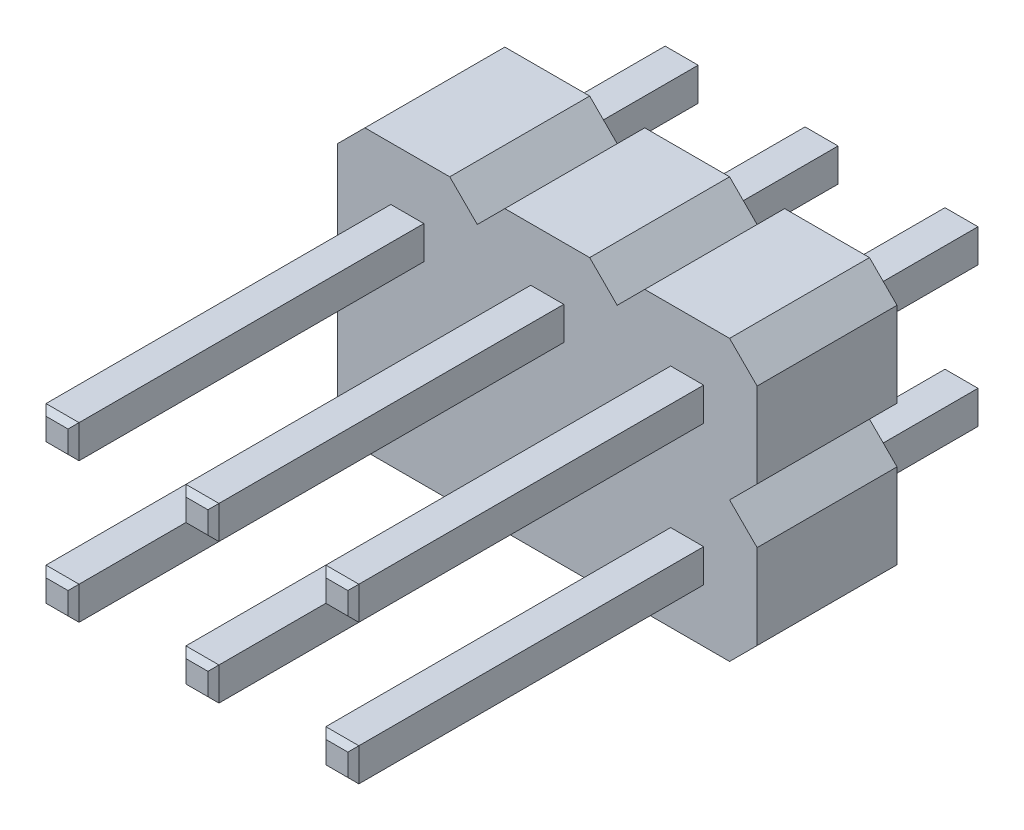
SolidWorks part; units mm, degrees
ref_plane "Front Plane" through (0, 0, 0) normal (0, 0, 1) x (1, 0, 0)
ref_plane "Top Plane" through (0, 0, 0) normal (0, 1, 0) x (1, 0, 0)
ref_plane "Right Plane" through (0, 0, 0) normal (1, 0, 0) x (0, 0, -1)
sketch "Sketch1" plane through (0, 0, 0) normal (0, 0, 1) x (1, 0, 0)
  line L0 (1.27, 0) -> (0, 0) construction
  line L5 (0, 0) -> (0, 1.27) construction
  line L6 (-0.77, 1.27) -> (0.77, 1.27)
  line L7 (0.77, 1.27) -> (1.27, 0.77)
  line L8 (1.27, 0.77) -> (1.27, -0.77)
  line L9 (-1.27, 0.77) -> (-1.27, -0.77)
  line L10 (-0.77, 1.27) -> (-1.27, 0.77)
  line L11 (0.77, -1.27) -> (1.27, -0.77)
  line L12 (-0.77, -1.27) -> (0.77, -1.27)
  line L13 (-0.77, -1.27) -> (-1.27, -0.77)
  point P13 (-1.27, 0)
  dimension "D1" = 1.27
  dimension "D2" = 45
  dimension "D3" = 0.5
extrude "Plastic" add sketch "Sketch1" along normal blind 2.54
sketch "Sketch2" plane through (0, 0, 0) normal (1, 0, 0) x (0, 0, -1)
  line L0 (-8.9, 0.3) -> (-8.9, -0.3)
  line L1 (-8.9, 0) -> (2.54, 0) construction
  line L4 (-8.9, -0.3) -> (2.54, -0.3)
  line L6 (-8.9, 0.3) -> (2.54, 0.3)
  line L8 (2.54, -0.3) -> (2.54, 0.3)
  line L11 (-9.5, 4.63) -> (-9.5, 0.6) construction
  line L12 (-9.8, 4.63) -> (-9.8, 0.6) construction
  line L13 (-9.2, 4.63) -> (-9.2, 0.6) construction
  arc A3 (-9.8, 0.6) -> (-8.9, -0.3) centre (-8.9, 0.6) ccw construction
  arc A4 (-9.5, 0.6) -> (-8.9, 0) centre (-8.9, 0.6) ccw construction
  arc A5 (-9.2, 0.6) -> (-8.9, 0.3) centre (-8.9, 0.6) ccw construction
  dimension "D1" = 8.9
  dimension "D4" = 2.54
  dimension "D2" = 0.3
  dimension "D3" = 0.3
extrude "Contact" add sketch "Sketch2" along normal mid plane 0.6
chamfer "Chamfer1" distance 0.1 angle 45 8 edges at (0.3, 0, -2.54) (0, -0.3, -2.54) (-0.3, 0, -2.54) (0, 0.3, -2.54) (-0.3, 0, 8.9) (0, 0.3, 8.9) (0.3, 0, 8.9) (0, -0.3, 8.9)
pattern_linear "Линейный массив1" count 3 spacing 2.54 along (1, 0, 0) count 2 spacing 2.54 along (0, 1, 0) of "Contact", "Plastic", "Chamfer1"
